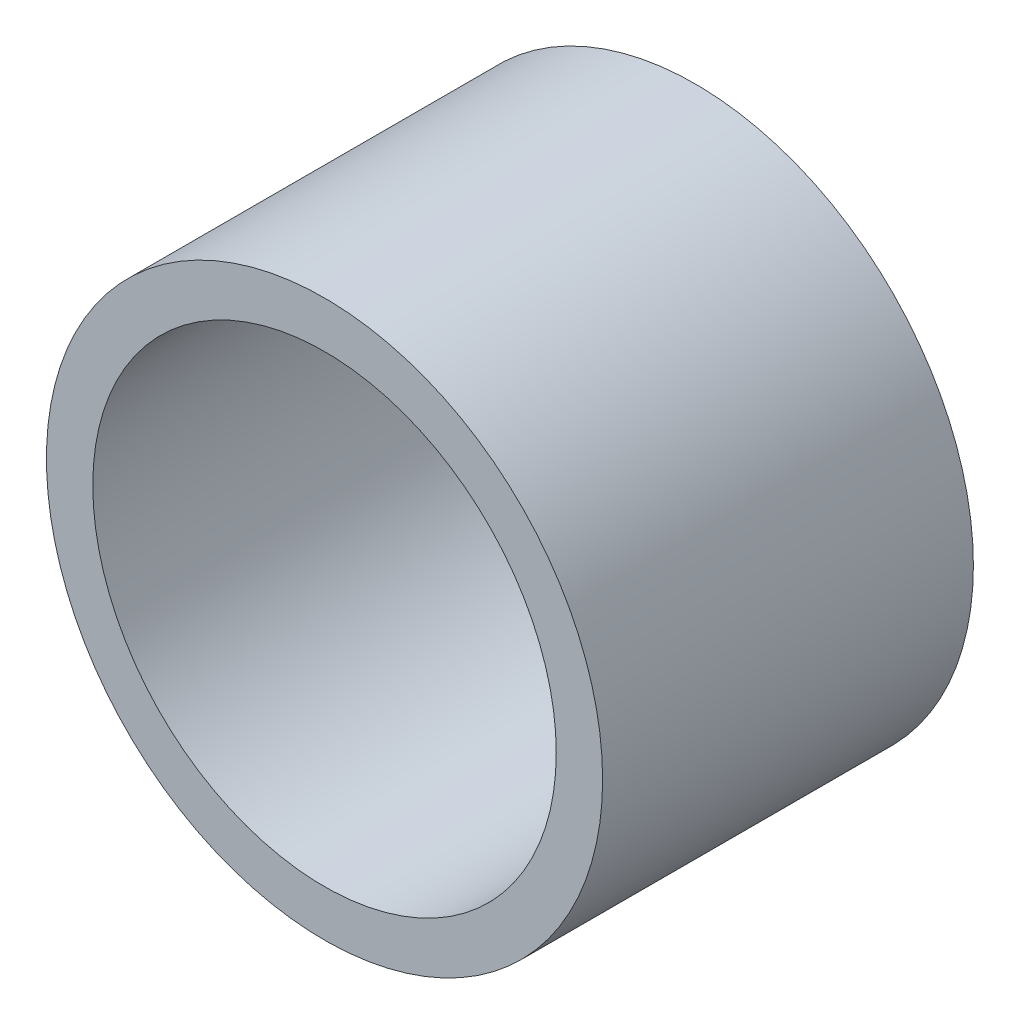
SolidWorks part; units mm, degrees
ref_plane "Alzado" through (0, 0, 0) normal (0, 0, 1) x (1, 0, 0)
ref_plane "Planta" through (0, 0, 0) normal (0, 1, 0) x (1, 0, 0)
ref_plane "Vista lateral" through (0, 0, 0) normal (1, 0, 0) x (0, 0, -1)
sketch "Croquis1" plane through (0, 0, 0) normal (0, 0, 1) x (1, 0, 0)
  circle A0 centre (0, 0) radius 15
  circle A1 centre (0, 0) radius 12.5
  dimension "D1" = 25
  dimension "D2" = 30
extrude "Saliente-Extruir1" add sketch "Croquis1" against normal blind 20
